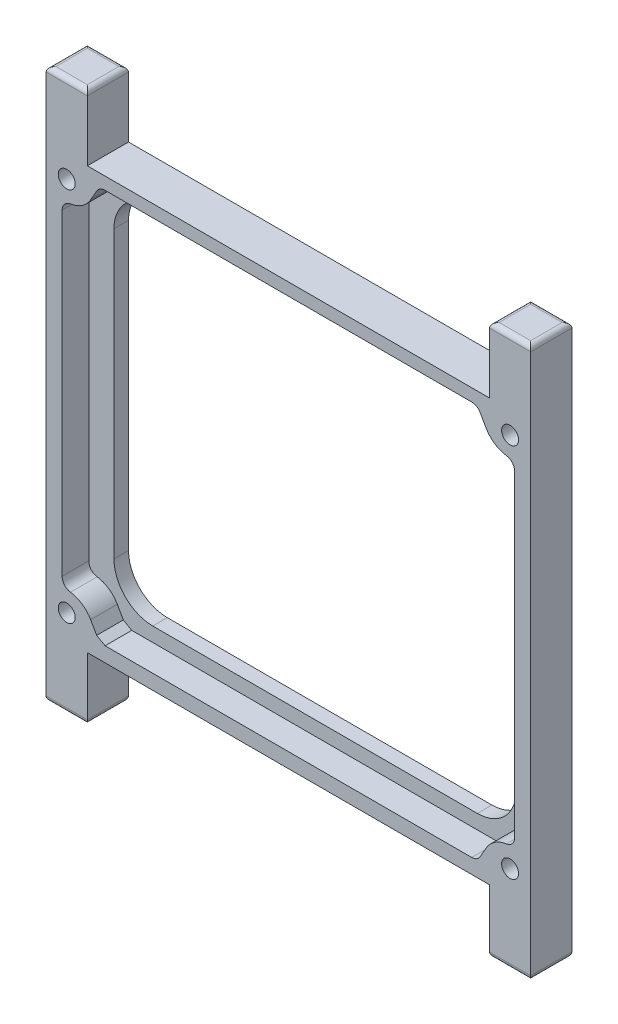
SolidWorks part; units mm, degrees
ref_plane "Front Plane" through (0, 0, 0) normal (0, 0, 1) x (1, 0, 0)
ref_plane "Top Plane" through (0, 0, 0) normal (0, 1, 0) x (1, 0, 0)
ref_plane "Right Plane" through (0, 0, 0) normal (1, 0, 0) x (0, 0, -1)
sketch "Sketch1" plane through (0, 0, 0) normal (0, 0, 1) x (1, 0, 0)
  line L1 (-50, 56.75) -> (50, 56.75)
  line L2 (-50, 56.75) -> (-50, -56.75)
  line L3 (-50, -56.75) -> (50, -56.75)
  line L4 (50, 56.75) -> (50, -56.75)
  line L5 (-50, 56.75) -> (50, -56.75) construction
  line L6 (-50, -56.75) -> (50, 56.75) construction
  point P0 (0, 0)
  dimension "D1" = 100
  dimension "D2" = 113.5
extrude "Boss-Extrude1" add sketch "Sketch1" along normal blind 8.5
sketch "Sketch2" plane through (0, 0, 8.5) normal (0, 0, 1) x (1, 0, 0)
  line L1 (50, 56.75) -> (-50, 56.75) construction
  line L2 (-41.5, 56.75) -> (-41.5, 43.25)
  line L3 (-50, -56.75) -> (50, -56.75) construction
  line L6 (0, -4.675) -> (0, 4.675) construction
  line L8 (41.5, 56.75) -> (41.5, 43.25)
  line L11 (-33.5, -37.75) -> (33.5, -37.75)
  line L12 (-41.5, 43.25) -> (41.5, 43.25)
  line L17 (-41.5, -0.25) -> (41.5, -0.25)
  line L18 (-41.5, -43.75) -> (41.5, -43.75)
  line L19 (-41.5, -29.75) -> (-41.5, -0.25)
  line L20 (41.5, -29.75) -> (41.5, -0.25)
  line L33 (41.5, -0.25) -> (41.5, -29.75)
  line L34 (-41.5, -0.25) -> (-41.5, -29.75)
  line L35 (-41.5, -43.75) -> (-41.5, -56.75)
  line L36 (41.5, -43.75) -> (41.5, -56.75)
  line L37 (-16.75, 27.75) -> (-6.75, 27.75)
  line L38 (-18.25, 29.25) -> (-5.25, 29.25)
  line L39 (-18.25, 29.25) -> (-18.25, 16.25)
  line L40 (-18.25, 16.25) -> (-5.25, 16.25)
  line L41 (-5.25, 29.25) -> (-5.25, 16.25)
  line L42 (-18.25, 29.25) -> (-5.25, 16.25) construction
  line L43 (-18.25, 16.25) -> (-5.25, 29.25) construction
  line L44 (-6.75, 27.75) -> (-6.75, 17.75)
  line L45 (-16.75, 17.75) -> (-6.75, 17.75)
  line L46 (-16.75, 27.75) -> (-16.75, 17.75)
  line L47 (-41.5, -56.75) -> (41.5, -56.75)
  line L48 (-41.5, 56.75) -> (41.5, 56.75)
  line L49 (50, -56.75) -> (50, 56.75) construction
  line L50 (4.675, 0) -> (-4.675, 0) construction
  line L51 (0, 43.25) -> (0, 0) construction
  line L52 (-11.75, 35.783) -> (-11.75, 12.7164) construction
  line L57 (16.75, 27.75) -> (16.75, 17.75)
  line L58 (16.75, 17.75) -> (6.75, 17.75)
  line L59 (6.75, 27.75) -> (6.75, 17.75)
  line L60 (16.75, 27.75) -> (6.75, 27.75)
  line L61 (28.5, 37.25) -> (23.5, 37.25)
  line L62 (23.5, 37.25) -> (23.5, 11.25)
  line L63 (41.5, 11.25) -> (23.5, 11.25)
  line L64 (41.5, 24.25) -> (41.5, 11.25)
  line L65 (6.75, 27.75) -> (16.75, 27.75)
  line L66 (16.75, 17.75) -> (6.75, 17.75)
  line L67 (23.5, 37.25) -> (23.5, 11.25)
  line L68 (41.5, 11.25) -> (41.5, 24.25)
  line L69 (23.5, 37.25) -> (28.5, 37.25)
  arc A0 (41.5, -29.75) -> (33.5, -37.75) centre (33.5, -29.75) cw
  arc A1 (-41.5, -29.75) -> (-33.5, -37.75) centre (-33.5, -29.75) ccw
  circle A4 centre (45.75, 38.75) radius 1.75
  circle A5 centre (45.75, -38.75) radius 1.75
  circle A6 centre (-45.75, 38.75) radius 1.75
  circle A7 centre (-45.75, -38.75) radius 1.75
  arc A8 (41.5, 24.25) -> (28.5, 37.25) centre (28.5, 24.25) ccw
  arc A9 (28.5, 37.25) -> (41.5, 24.25) centre (28.5, 24.25) cw
  point P0 (45.75, 38.75)
  point P22 (-11.75, 22.75)
  point P63 (-11.75, 22.75)
  dimension "D2" = 13
  dimension "D3" = 13.5
  dimension "D6" = 113.5
  dimension "D8" = 6
  dimension "D11" = 13
  dimension "D12" = 13
  dimension "D14" = 18
  dimension "D15" = 4.25
  dimension "D13" = 1.5
extrude "Cut-Extrude1" cut sketch "Sketch2" against normal up to next
ref_plane "Plane1" through (0, 0, 3) normal (0, 0, -1) x (-1, 0, 0)
sketch "Sketch6" plane through (0, 0, 8.5) normal (0, 0, 1) x (1, 0, 0)
  line L8 (50, -56.75) -> (50, 56.75) construction
  line L10 (41.5, 8.25) -> (41.5, 29.25)
  line L11 (33.5, 8.25) -> (41.5, 8.25)
  line L14 (6.75, 17.75) -> (16.75, 17.75)
  line L15 (6.75, 27.75) -> (6.75, 17.75)
  line L16 (16.75, 27.75) -> (6.75, 27.75)
  line L17 (16.75, 17.75) -> (16.75, 27.75)
  line L21 (33.5, 37.25) -> (28.5, 37.25)
  line L22 (28.5, 37.25) -> (28.5, 8.25)
  line L23 (28.5, 8.25) -> (33.5, 8.25)
  line L24 (0, -4.675) -> (0, 4.675) construction
  line L25 (-41.5, 8.25) -> (-41.5, 29.25)
  line L26 (-33.5, 8.25) -> (-41.5, 8.25)
  line L27 (-28.5, 8.25) -> (-33.5, 8.25)
  line L28 (-28.5, 37.25) -> (-28.5, 8.25)
  line L29 (-33.5, 37.25) -> (-28.5, 37.25)
  arc A1 (41.5, 29.25) -> (33.5, 37.25) centre (33.5, 29.25) ccw
  arc A2 (-41.5, 29.25) -> (-33.5, 37.25) centre (-33.5, 29.25) cw
  dimension "D1" = 8.5
  dimension "D2" = 5
extrude "Cut-Extrude2" cut sketch "Sketch6" against normal up to next
sketch "Sketch8" plane through (0, 0, 8.5) normal (0, 0, 1) x (1, 0, 0)
  line L0 (-37.835, -40.7) -> (37.835, -40.7)
  line L1 (-41.5, -43.75) -> (41.5, -43.75) construction
  line L2 (-37.835, -40.7) -> (-39.5671, -39.7)
  line L3 (-39.5671, -39.7) -> (-40.8111, -37.52)
  line L4 (0, -4.675) -> (0, 4.675) construction
  line L5 (39.5671, -39.7) -> (40.8111, -37.52)
  line L6 (4.675, 0) -> (-4.675, 0) construction
  line L7 (39.5671, 39.7) -> (40.8111, 37.52)
  line L8 (-39.5671, 39.7) -> (-40.8111, 37.52)
  line L9 (46.7011, 32.72) -> (46.7011, -32.72)
  line L10 (-46.7011, -32.72) -> (-46.7011, 32.72)
  line L11 (-37.835, 40.7) -> (37.835, 40.7)
  arc A0 (-39.5671, -39.7) -> (-37.835, -40.7) centre (-37.845, -38.7172) ccw
  arc A1 (-44.9811, -34.7) -> (-40.8111, -37.52) centre (-45.7922, -40.3925) cw
  arc A2 (-46.7011, -32.72) -> (-44.9811, -34.7) centre (-44.7011, -32.7197) ccw
  arc A3 (39.5671, -39.7) -> (37.835, -40.7) centre (37.845, -38.7172) cw
  arc A4 (44.9811, -34.7) -> (40.8111, -37.52) centre (45.7922, -40.3925) ccw
  arc A5 (46.7011, -32.72) -> (44.9811, -34.7) centre (44.7011, -32.7197) cw
  arc A6 (39.5671, 39.7) -> (37.835, 40.7) centre (37.845, 38.7172) ccw
  arc A7 (46.7011, 32.72) -> (44.9811, 34.7) centre (44.7011, 32.7197) ccw
  arc A8 (44.9811, 34.7) -> (40.8111, 37.52) centre (45.7922, 40.3925) cw
  arc A9 (-39.5671, 39.7) -> (-37.835, 40.7) centre (-37.845, 38.7172) cw
  arc A10 (-44.9811, 34.7) -> (-40.8111, 37.52) centre (-45.7922, 40.3925) ccw
  arc A11 (-46.7011, 32.72) -> (-44.9811, 34.7) centre (-44.7011, 32.7197) cw
  point P4 (0, -40.7)
  point P5 (0, -43.75)
  point P8 (-44.9811, -34.7)
  point P10 (-46.7011, -32.72)
  line M7 (41.5, 8.25) -> (28.5, 8.25)
  arc M10 (33.5, 37.25) -> (41.5, 29.25) centre (33.5, 29.25) cw
  line M11 (41.5, 29.25) -> (41.5, 8.25)
  line M12 (6.75, 17.75) -> (6.75, 27.75)
  line M13 (6.75, 27.75) -> (16.75, 27.75)
  line M14 (16.75, 27.75) -> (16.75, 17.75)
  line M15 (16.75, 17.75) -> (6.75, 17.75)
  arc M31 (-33.5, -37.75) -> (-41.5, -29.75) centre (-33.5, -29.75) cw
  line M32 (-41.5, -29.75) -> (-41.5, -0.25)
  line M33 (-41.5, -0.25) -> (41.5, -0.25)
  line M34 (41.5, -0.25) -> (41.5, -29.75)
  arc M35 (41.5, -29.75) -> (33.5, -37.75) centre (33.5, -29.75) cw
  line M36 (33.5, -37.75) -> (-33.5, -37.75)
  line M37 (-16.75, 17.75) -> (-16.75, 27.75)
  line M38 (-16.75, 27.75) -> (-6.75, 27.75)
  line M39 (-6.75, 27.75) -> (-6.75, 17.75)
  line M40 (-6.75, 17.75) -> (-16.75, 17.75)
  line M68 (28.5, 8.25) -> (28.5, 37.25)
  line M69 (28.5, 37.25) -> (33.5, 37.25)
  arc M70 (-41.5, 29.25) -> (-33.5, 37.25) centre (-33.5, 29.25) cw
  line M71 (-33.5, 37.25) -> (-28.5, 37.25)
  line M72 (-28.5, 37.25) -> (-28.5, 8.25)
  line M73 (-28.5, 8.25) -> (-41.5, 8.25)
  line M74 (-41.5, 8.25) -> (-41.5, 29.25)
  dimension "D5" = 2.51
  dimension "D9" = 1.98
  dimension "D1" = 3.05
  dimension "D2" = 75.67
  dimension "D3" = 2
  dimension "D4" = 1
  dimension "D6" = 2.18
  dimension "D7" = 2.82
  dimension "D8" = 4.17
  dimension "D10" = 1.72
fillet "Fillet1" radius 1 16 edges at (45.75, 56.75, 8.5) (50, 56.75, 4.25) (45.75, 56.75, 0) (41.5, 56.75, 4.25) (-41.5, 56.75, 4.25) (-45.75, 56.75, 0) (-50, 56.75, 4.25) (-45.75, 56.75, 8.5) (-50, -56.75, 4.25) (-45.75, -56.75, 8.5) (-41.5, -56.75, 4.25) (-45.75, -56.75, 0) (45.75, -56.75, 8.5) (41.5, -56.75, 4.25) (45.75, -56.75, 0) (50, -56.75, 4.25)
extrude "Cut-Extrude5" cut sketch "Sketch8" against normal blind 5.5 contours A11 L10 A2 A1 L3 L2 L0 A3 L5 A4 A5 L9 A7 A8 L7 A6 L11 A9 L8 A10 M40 M37 M38 M39 M36 M31 M32 M33 M34 M35 M15 M12 M13 M14 M74 M70 M71 M72 M73 M7 M68 M69 M10 M11
sketch "Sketch9" plane through (0, 0, 3) normal (0, 0, 1) x (1, 0, 0)
  line L1 (-33.5, -37.75) -> (33.5, -37.75)
  line L2 (41.5, -29.75) -> (41.5, 29.25)
  line L3 (-41.5, 29.25) -> (-41.5, -29.75)
  line L5 (-33.5, 37.25) -> (33.5, 37.25)
  arc A0 (-41.5, -29.75) -> (-33.5, -37.75) centre (-33.5, -29.75) ccw
  arc A1 (33.5, -37.75) -> (41.5, -29.75) centre (33.5, -29.75) ccw
  arc A2 (41.5, 29.25) -> (33.5, 37.25) centre (33.5, 29.25) ccw
  arc A3 (-41.5, 29.25) -> (-33.5, 37.25) centre (-33.5, 29.25) cw
extrude "Cut-Extrude6" cut sketch "Sketch9" against normal through all
